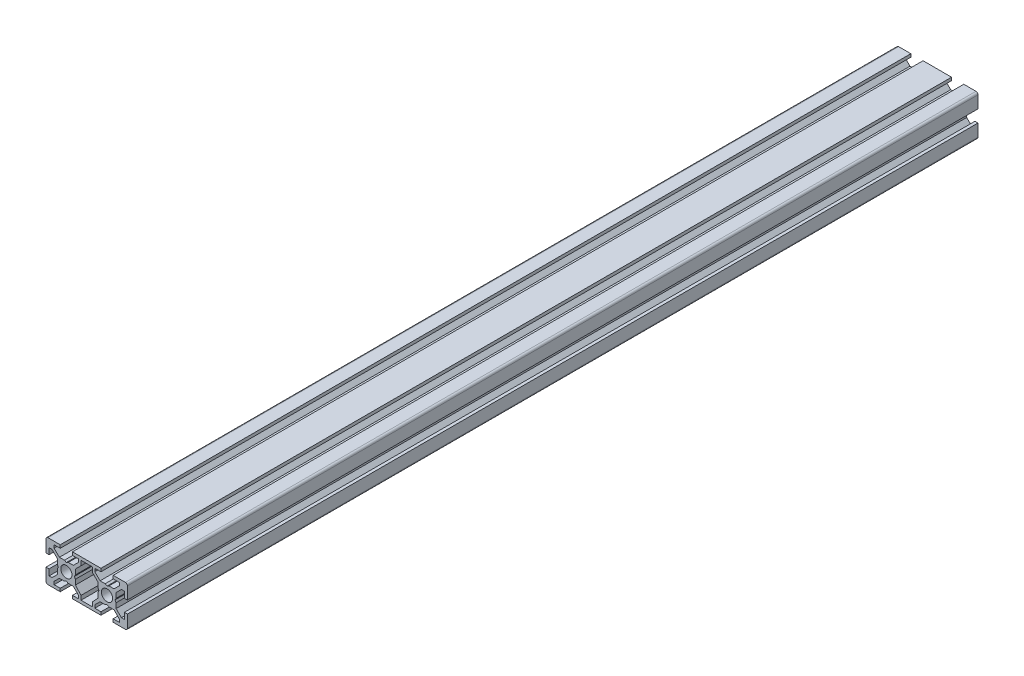
SolidWorks part; units mm, degrees
ref_plane "Front Plane" through (0, 0, 0) normal (0, 0, 1) x (1, 0, 0)
ref_plane "Top Plane" through (0, 0, 0) normal (0, 1, 0) x (1, 0, 0)
ref_plane "Right Plane" through (0, 0, 0) normal (1, 0, 0) x (0, 0, -1)
sketch "Sketch1" plane through (0, 0, 0) normal (0, 0, 1) x (1, 0, 0)
  line L0 (-707.1068, -707.1068) -> (34648.2323, 34648.2323) construction
  line L1 (-3.0018, 10) -> (-10, 10)
  line L2 (0.9376, 4.4579) -> (-0.0011, 3.9339)
  line L3 (3.4252, 4.4579) -> (0.9376, 4.4579)
  line L4 (6.0128, 7.0454) -> (3.4252, 4.4579)
  line L5 (0, -1000) -> (0, 49000) construction
  line L6 (-1000, 0) -> (49000, 0) construction
  line L7 (6.0128, 8.5) -> (6.0128, 7.0454)
  line L8 (3.0018, 8.5) -> (6.0128, 8.5)
  line L9 (3.0018, 10) -> (16.9982, 10)
  line L10 (3.0018, 8.5) -> (3.0018, 10)
  line L11 (-707.1068, 707.1068) -> (34648.2323, -34648.2323) construction
  line L12 (-7.0458, 6.0144) -> (-4.4582, 3.4268)
  line L13 (-8.5008, 6.0144) -> (-7.0458, 6.0144)
  line L14 (-8.5008, 3.0018) -> (-8.5008, 6.0144)
  line L15 (0, -0.0423) -> (0.0002, 2.0704) construction
  line L16 (-10, 3.0018) -> (-10, 10)
  line L17 (-8.5008, 3.0018) -> (-10, 3.0018)
  line L18 (7.2087, -6.4198) -> (7.2087, -8.5)
  line L19 (7.2087, -8.5) -> (12.7913, -8.5)
  line L20 (7.2087, 6.1776) -> (7.2087, 8.5)
  line L21 (7.2087, 8.5) -> (12.7913, 8.5)
  line L22 (7.2087, 6.1776) -> (4.4583, 3.4262)
  line L23 (-3.0018, 8.5) -> (-3.0018, 10)
  line L24 (-3.0018, 8.5) -> (-6.0148, 8.5)
  line L25 (-6.0148, 8.5) -> (-6.0148, 7.0458)
  line L26 (-6.0148, 7.0458) -> (-3.4272, 4.4582)
  line L27 (-3.4272, 4.4582) -> (-0.9396, 4.4582)
  line L28 (-0.9396, 4.4582) -> (-0.0011, 3.9339)
  line L29 (-4.4582, 3.4268) -> (-4.4582, 0.9396)
  line L30 (-4.4582, 0.9396) -> (-3.9347, 0)
  line L31 (4.4575, 0.9396) -> (3.9347, 0)
  line L32 (4.4583, 3.4262) -> (4.4575, 0.9396)
  line L33 (10, -990) -> (10, 49010) construction
  line L34 (19.0624, -4.4579) -> (20.0011, -3.9339)
  line L35 (16.5748, -4.4579) -> (19.0624, -4.4579)
  line L36 (13.9872, -7.0454) -> (16.5748, -4.4579)
  line L37 (-0.9396, -4.4582) -> (-0.0011, -3.9339)
  line L38 (13.9872, -8.5) -> (13.9872, -7.0454)
  line L39 (16.9982, -8.5) -> (13.9872, -8.5)
  line L40 (16.9982, -8.5) -> (16.9982, -10)
  line L41 (24.4575, -0.9396) -> (23.9347, 0)
  line L42 (24.4582, -3.4268) -> (24.4575, -0.9396)
  line L43 (27.0458, -6.0144) -> (24.4582, -3.4268)
  line L44 (28.5008, -6.0144) -> (27.0458, -6.0144)
  line L45 (-3.4272, -4.4582) -> (-0.9396, -4.4582)
  line L46 (-6.0148, -7.0458) -> (-3.4272, -4.4582)
  line L47 (-6.0148, -8.5) -> (-6.0148, -7.0458)
  line L48 (-3.0018, -8.5) -> (-6.0148, -8.5)
  line L49 (-3.0018, -10) -> (-10, -10)
  line L50 (-3.0018, -8.5) -> (-3.0018, -10)
  line L51 (4.4588, -0.9386) -> (3.9347, 0)
  line L52 (4.4583, -3.4262) -> (4.4588, -0.9386)
  line L53 (7.2087, -6.4198) -> (4.4583, -3.4262)
  line L54 (28.5008, -3.0018) -> (28.5008, -6.0144)
  line L55 (30, -3.0018) -> (30, -10)
  line L56 (28.5008, -3.0018) -> (30, -3.0018)
  line L57 (12.7913, -6.4198) -> (15.5417, -3.4262)
  line L58 (-8.5008, -3.0018) -> (-10, -3.0018)
  line L59 (-10, -3.0018) -> (-10, -10)
  line L60 (-8.5008, -3.0018) -> (-8.5008, -6.0144)
  line L61 (-8.5008, -6.0144) -> (-7.0458, -6.0144)
  line L62 (-7.0458, -6.0144) -> (-4.4582, -3.4268)
  line L63 (-4.4582, -3.4268) -> (-4.4575, -0.9396)
  line L64 (-4.4575, -0.9396) -> (-3.9347, 0)
  line L65 (3.0018, -8.5) -> (3.0018, -10)
  line L66 (3.0018, -10) -> (16.9982, -10)
  line L67 (3.0018, -8.5) -> (6.0128, -8.5)
  line L68 (6.0128, -8.5) -> (6.0128, -7.0454)
  line L69 (6.0128, -7.0454) -> (3.4252, -4.4579)
  line L70 (3.4252, -4.4579) -> (0.9376, -4.4579)
  line L71 (0.9376, -4.4579) -> (-0.0011, -3.9339)
  line L72 (15.5417, -3.4262) -> (15.5412, -0.9386)
  line L73 (15.5412, -0.9386) -> (16.0653, 0)
  line L74 (23.0018, -8.5) -> (23.0018, -10)
  line L75 (23.0018, -10) -> (30, -10)
  line L76 (23.0018, -8.5) -> (26.0148, -8.5)
  line L77 (26.0148, -8.5) -> (26.0148, -7.0458)
  line L78 (26.0148, -7.0458) -> (23.4272, -4.4582)
  line L79 (23.4272, -4.4582) -> (20.9396, -4.4582)
  line L80 (20.9396, -4.4582) -> (20.0011, -3.9339)
  line L81 (15.5417, 3.4262) -> (15.5425, 0.9396)
  line L82 (15.5425, 0.9396) -> (16.0653, 0)
  line L83 (24.4582, 0.9396) -> (23.9347, 0)
  line L84 (24.4582, 3.4268) -> (24.4582, 0.9396)
  line L85 (20.9396, 4.4582) -> (20.0011, 3.9339)
  line L86 (23.4272, 4.4582) -> (20.9396, 4.4582)
  line L87 (26.0148, 7.0458) -> (23.4272, 4.4582)
  line L88 (26.0148, 8.5) -> (26.0148, 7.0458)
  line L89 (23.0018, 8.5) -> (26.0148, 8.5)
  line L90 (23.0018, 8.5) -> (23.0018, 10)
  line L91 (12.7913, 6.1776) -> (15.5417, 3.4262)
  line L92 (12.7913, 6.1776) -> (12.7913, 8.5)
  line L93 (12.7913, -6.4198) -> (12.7913, -8.5)
  line L94 (28.5008, 3.0018) -> (30, 3.0018)
  line L95 (30, 3.0018) -> (30, 10)
  line L96 (28.5008, 3.0018) -> (28.5008, 6.0144)
  line L97 (28.5008, 6.0144) -> (27.0458, 6.0144)
  line L98 (27.0458, 6.0144) -> (24.4582, 3.4268)
  line L99 (16.9982, 8.5) -> (16.9982, 10)
  line L100 (16.9982, 8.5) -> (13.9872, 8.5)
  line L101 (13.9872, 8.5) -> (13.9872, 7.0454)
  line L102 (13.9872, 7.0454) -> (16.5748, 4.4579)
  line L103 (16.5748, 4.4579) -> (19.0624, 4.4579)
  line L104 (19.0624, 4.4579) -> (20.0011, 3.9339)
  line L105 (23.0018, 10) -> (30, 10)
  circle A0 centre (0, 0) radius 2.75
  circle A1 centre (20, 0) radius 2.75
  point P76 (10, -10)
  point P79 (10, -10)
  point P88 (10, -3.0018)
  point P111 (10, 8.5)
  point P112 (10, -8.5)
  point P114 (10, 3.0018)
  point P120 (10, 10)
  point P121 (10, 10)
extrude "Boss-Extrude1" add sketch "Sketch1" along normal blind 418
fillet "Fillet2" radius 1 1 edges at (-10, -10, 209)
fillet "Fillet4" radius 1 1 edges at (-10, 10, 209)
fillet "Fillet5" radius 1 1 edges at (30, 10, 209)
fillet "Fillet6" radius 1 1 edges at (30, -10, 209)
